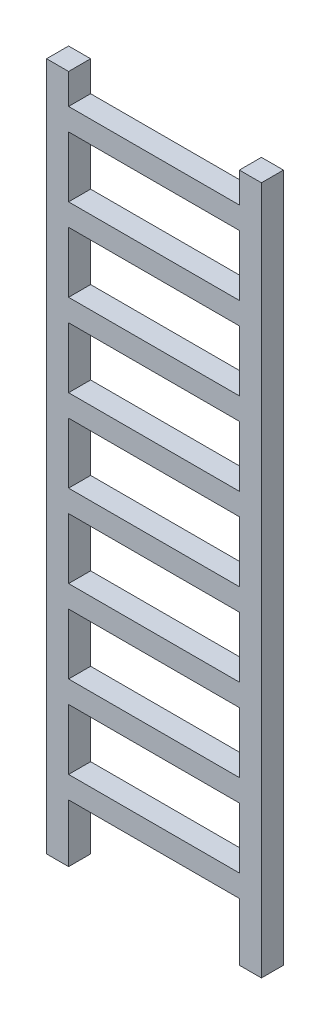
SolidWorks part; units mm, degrees
ref_plane "前视基准面" through (0, 0, 0) normal (0, 0, 1) x (1, 0, 0)
ref_plane "上视基准面" through (0, 0, 0) normal (0, 1, 0) x (1, 0, 0)
ref_plane "右视基准面" through (0, 0, 0) normal (1, 0, 0) x (0, 0, -1)
other "Configuration Table"
sketch "草图1" plane through (0, 0, 0) normal (0, 0, 1) x (1, 0, 0)
  line L1 (-390, -1250) -> (-310, -1250)
  line L2 (-390, -1250) -> (-390, 1250)
  line L3 (-390, 1250) -> (-310, 1250)
  line L4 (-310, -1250) -> (-310, 1250)
  line L5 (-390, -1250) -> (-310, 1250) construction
  line L6 (-390, 1250) -> (-310, -1250) construction
extrude "凸台-拉伸1" add sketch "草图1" along normal blind 80
sketch "草图2" plane through (0, 0, 0) normal (0, 0, 1) x (1, 0, 0)
  line L1 (310, -1250) -> (390, -1250)
  line L2 (310, -1250) -> (310, 1250)
  line L3 (310, 1250) -> (390, 1250)
  line L4 (390, -1250) -> (390, 1250)
  line L5 (310, -1250) -> (390, 1250) construction
  line L6 (310, 1250) -> (390, -1250) construction
extrude "凸台-拉伸2" add sketch "草图2" along normal blind 80
sketch "草图3" plane through (0, 0, 0) normal (0, 0, 1) x (1, 0, 0)
  line L1 (-350, 1060) -> (350, 1060)
  line L2 (-350, 1060) -> (-350, 1140)
  line L3 (-350, 1140) -> (350, 1140)
  line L4 (350, 1060) -> (350, 1140)
  line L5 (-350, 1060) -> (350, 1140) construction
  line L6 (-350, 1140) -> (350, 1060) construction
extrude "凸台-拉伸3" add sketch "草图3" along normal blind 80
sketch "草图4" plane through (0, 0, 0) normal (0, 0, 1) x (1, 0, 0)
  line L1 (-350, 760) -> (350, 760)
  line L2 (-350, 760) -> (-350, 840)
  line L3 (-350, 840) -> (350, 840)
  line L4 (350, 760) -> (350, 840)
  line L5 (-350, 760) -> (350, 840) construction
  line L6 (-350, 840) -> (350, 760) construction
extrude "凸台-拉伸4" add sketch "草图4" along normal blind 80
sketch "草图5" plane through (0, 0, 0) normal (0, 0, 1) x (1, 0, 0)
  line L1 (-350, 460) -> (350, 460)
  line L2 (-350, 460) -> (-350, 540)
  line L3 (-350, 540) -> (350, 540)
  line L4 (350, 460) -> (350, 540)
  line L5 (-350, 460) -> (350, 540) construction
  line L6 (-350, 540) -> (350, 460) construction
extrude "凸台-拉伸5" add sketch "草图5" along normal blind 80
sketch "草图6" plane through (0, 0, 0) normal (0, 0, 1) x (1, 0, 0)
  line L1 (-350, 160) -> (350, 160)
  line L2 (-350, 160) -> (-350, 240)
  line L3 (-350, 240) -> (350, 240)
  line L4 (350, 160) -> (350, 240)
  line L5 (-350, 160) -> (350, 240) construction
  line L6 (-350, 240) -> (350, 160) construction
  point P0 (0, 200)
extrude "凸台-拉伸6" add sketch "草图6" along normal blind 80
sketch "草图7" plane through (0, 0, 0) normal (0, 0, 1) x (1, 0, 0)
  line L1 (-350, -140) -> (350, -140)
  line L2 (-350, -140) -> (-350, -60)
  line L3 (-350, -60) -> (350, -60)
  line L4 (350, -140) -> (350, -60)
  line L5 (-350, -140) -> (350, -60) construction
  line L6 (-350, -60) -> (350, -140) construction
  point P0 (0, -100)
extrude "凸台-拉伸7" add sketch "草图7" along normal blind 80
sketch "草图8" plane through (0, 0, 0) normal (0, 0, 1) x (1, 0, 0)
  line L1 (-350, -440) -> (350, -440)
  line L2 (-350, -440) -> (-350, -360)
  line L3 (-350, -360) -> (350, -360)
  line L4 (350, -440) -> (350, -360)
  line L5 (-350, -440) -> (350, -360) construction
  line L6 (-350, -360) -> (350, -440) construction
  point P0 (0, -400)
extrude "凸台-拉伸8" add sketch "草图8" along normal blind 80
sketch "草图9" plane through (0, 0, 0) normal (0, 0, 1) x (1, 0, 0)
  line L1 (-350, -740) -> (350, -740)
  line L2 (-350, -740) -> (-350, -660)
  line L3 (-350, -660) -> (350, -660)
  line L4 (350, -740) -> (350, -660)
  line L5 (-350, -740) -> (350, -660) construction
  line L6 (-350, -660) -> (350, -740) construction
  point P0 (0, -700)
extrude "凸台-拉伸9" add sketch "草图9" along normal blind 80
sketch "草图10" plane through (0, 0, 0) normal (0, 0, 1) x (1, 0, 0)
  line L1 (-350, -1040) -> (350, -1040)
  line L2 (-350, -1040) -> (-350, -960)
  line L3 (-350, -960) -> (350, -960)
  line L4 (350, -1040) -> (350, -960)
  line L5 (-350, -1040) -> (350, -960) construction
  line L6 (-350, -960) -> (350, -1040) construction
  point P0 (0, -1000)
extrude "凸台-拉伸10" add sketch "草图10" along normal blind 80
